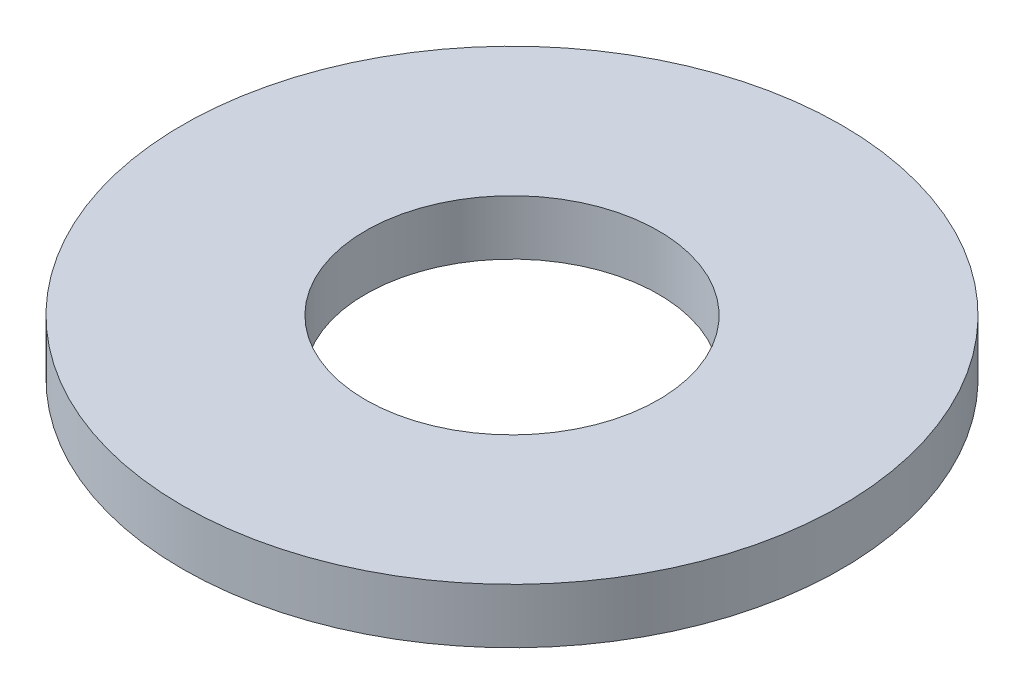
SolidWorks part; units mm, degrees
ref_plane "Front Plane" through (0, 0, 0) normal (0, 0, 1) x (1, 0, 0)
ref_plane "Top Plane" through (0, 0, 0) normal (0, 1, 0) x (1, 0, 0)
ref_plane "Right Plane" through (0, 0, 0) normal (1, 0, 0) x (0, 0, -1)
sketch "Sketch1" plane through (0, 0, 0) normal (0, 1, 0) x (1, 0, 0)
  circle A0 centre (0, 0) radius 4
  circle A1 centre (0, 0) radius 9
extrude "Boss-Extrude1" add sketch "Sketch1" along normal blind 1.5
